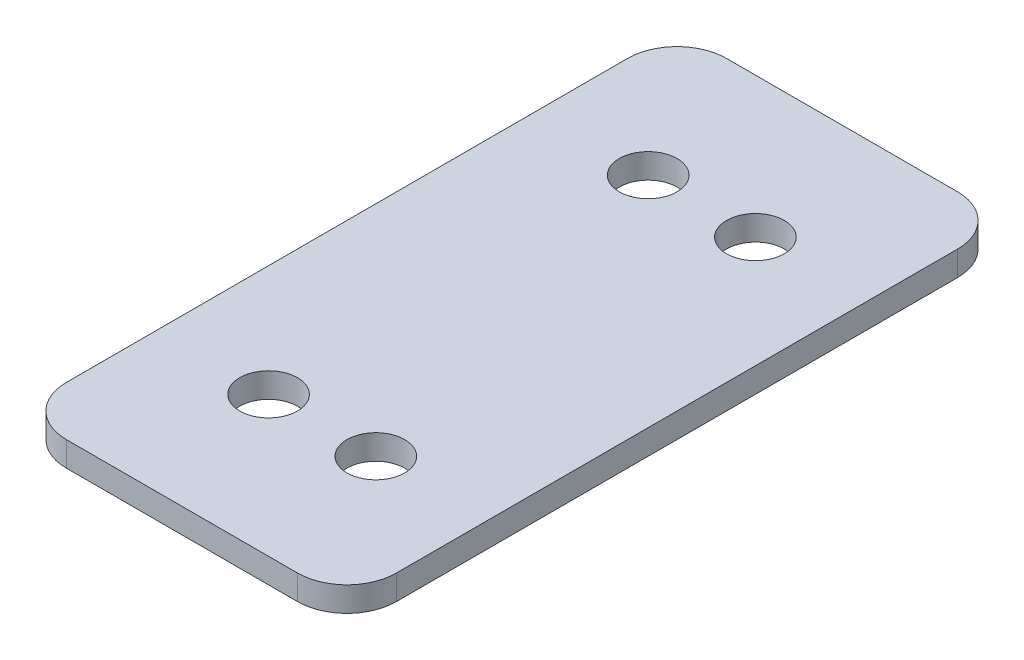
SolidWorks part; units mm, degrees
material "ABS"
ref_plane "Ebene vorne" through (0, 0, 0) normal (0, 0, 1) x (1, 0, 0)
ref_plane "Ebene oben" through (0, 0, 0) normal (0, 1, 0) x (1, 0, 0)
ref_plane "Ebene rechts" through (0, 0, 0) normal (1, 0, 0) x (0, 0, -1)
sketch "Skizze1" plane through (0, 0, 0) normal (0, 0, 1) x (1, 0, 0)
  line L0 (0, 0) -> (0, 19.0828) construction
  line L2 (-20, 0) -> (20, 0)
  line L3 (-20, 0) -> (-20, -3)
  line L4 (-20, -3) -> (20, -3)
  line L5 (20, 0) -> (20, -3)
  dimension "D1" = 40
  dimension "D2" = 3
extrude "Aufsatz-Linear austragen1" add sketch "Skizze1" along normal mid plane 80
fillet "Verrundung1" radius 6 4 edges at (20, -1.5, -40) (-20, -1.5, -40) (-20, -1.5, 40) (20, -1.5, 40)
sketch "Skizze2" plane through (0, 0, 0) normal (0, 1, 0) x (1, 0, 0)
  line L0 (0, 0) -> (23.299, 0) construction
  line L1 (0, 0) -> (0, 41.5434) construction
  circle A0 centre (6.5, 23) radius 3.5
  circle A1 centre (-6.5, 23) radius 3.5
  circle A2 centre (6.5, -23) radius 3.5
  circle A3 centre (-6.5, -23) radius 3.5
  dimension "D1" = 46
  dimension "D2" = 13
  dimension "D3" = 7
extrude "Schnitt-Linear austragen1" cut sketch "Skizze2" against normal blind 10
